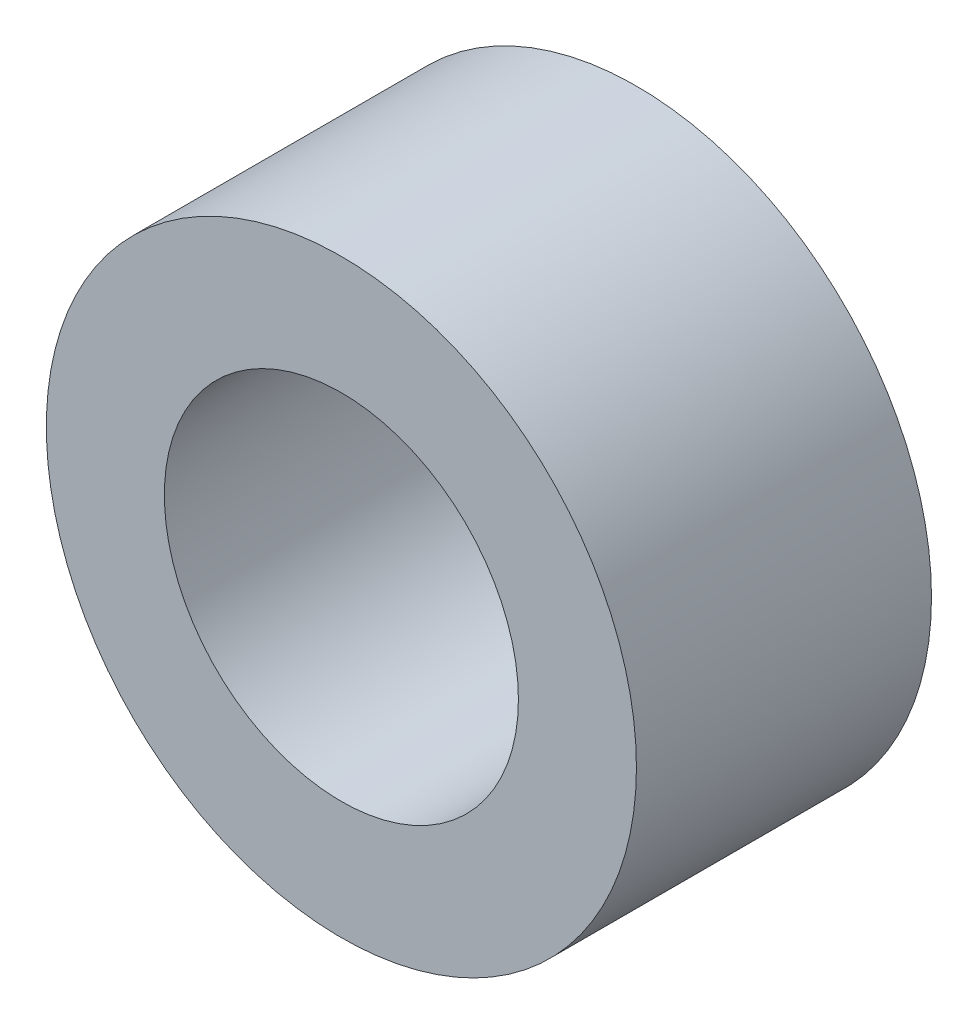
SolidWorks part; units mm, degrees
ref_plane "Front Plane" through (0, 0, 0) normal (0, 0, 1) x (1, 0, 0)
ref_plane "Top Plane" through (0, 0, 0) normal (0, 1, 0) x (1, 0, 0)
ref_plane "Right Plane" through (0, 0, 0) normal (1, 0, 0) x (0, 0, -1)
sketch "Sketch1" plane through (0, 0, 0) normal (0, 0, 1) x (1, 0, 0)
  circle A0 centre (0, 0) radius 5
  circle A1 centre (0, 0) radius 3
  dimension "D1" = 6
  dimension "D2" = 10
extrude "Boss-Extrude1" add sketch "Sketch1" along normal blind 5
